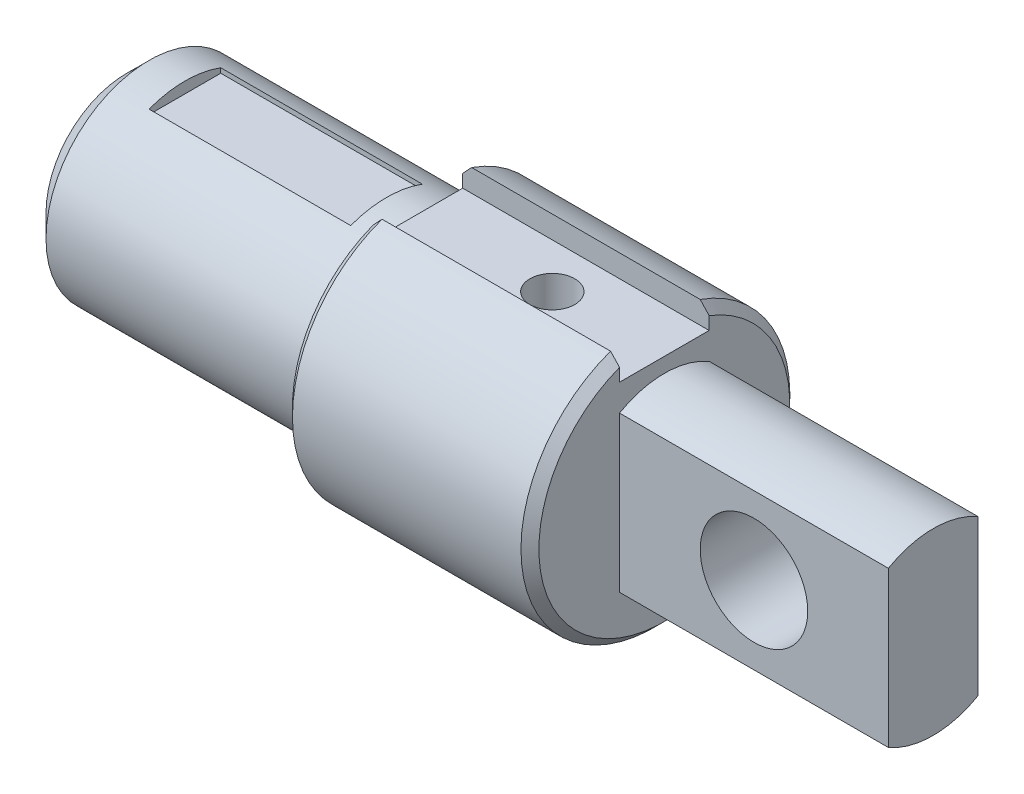
SolidWorks part; units mm, degrees
ref_plane "Спереди" through (0, 0, 0) normal (0, 0, 1) x (1, 0, 0)
ref_plane "Сверху" through (0, 0, 0) normal (0, 1, 0) x (1, 0, 0)
ref_plane "Справа" through (0, 0, 0) normal (1, 0, 0) x (0, 0, -1)
sketch "Эскиз1" plane through (0, 0, 0) normal (0, 0, 1) x (1, 0, 0)
  line L0 (0, 0) -> (-96.5352, 0) construction
  line L1 (0, 0) -> (0, 23)
  line L2 (0, 23) -> (65, 23)
  line L3 (65, 23) -> (65, 30)
  line L4 (65, 30) -> (120, 30)
  line L5 (120, 30) -> (120, 20)
  line L6 (120, 20) -> (180, 20)
  line L7 (180, 20) -> (180, 0)
  line L8 (180, 0) -> (0, 0)
  dimension "D1" = 46
  dimension "D2" = 60
  dimension "D3" = 40
  dimension "D4" = 65
  dimension "D5" = 60
  dimension "D6" = 180
revolve "Повернуть1" add sketch "Эскиз1" angle 360 about L0
sketch "Эскиз2" plane through (0, 0, 0) normal (0, 0, 1) x (1, 0, 0)
  line L0 (65, 23) -> (0, 23) construction
  line L1 (13, 23) -> (58, 23)
  line L2 (13, 23) -> (13, 20.5)
  line L3 (13, 20.5) -> (58, 20.5)
  line L4 (58, 23) -> (58, 20.5)
  line L5 (65, 30) -> (65, -30) construction
  dimension "D1" = 2.5
  dimension "D2" = 45
  dimension "D3" = 7
extrude "Вырез-Вытянуть1" cut sketch "Эскиз2" against normal mid plane 16
sketch "Эскиз4" plane through (65, 0, 0) normal (-1, 0, 0) x (0, 0, 1)
  line L0 (0, 30) -> (0, 0) construction
  line L2 (-10, 23.2843) -> (10, 23.2843)
  line L3 (-10, 23.2843) -> (-10, 30)
  line L4 (-10, 30) -> (10, 30)
  line L5 (10, 23.2843) -> (10, 30)
  line L6 (-10, 23.2843) -> (10, 30) construction
  line L7 (-10, 30) -> (10, 23.2843) construction
  circle A0 centre (0, 0) radius 30 construction
  point P5 (0, 26.6421)
  point P10 (10, 28.2843)
  dimension "D1" = 20
  dimension "D2" = 5
extrude "Вырез-Вытянуть2" cut sketch "Эскиз4" against normal through all
hole_wizard "Диаметр отверстия Ø10.0 (10)1" positions "Эскиз5" profile "Эскиз6" hole size "Ø10.0" standard "ISO"
sketch "Эскиз5" plane through (0, 23.2843, 0) normal (0, 1, 0) x (1, 0, 0)
  line L0 (65, 10) -> (65, -10) construction
  line L1 (65, 0) -> (120, 0) construction
  line L2 (65, 23) -> (65, -23) construction
  line L3 (120, -10) -> (120, 10) construction
  point P0 (95, 0)
  dimension "D1" = 30
sketch "Эскиз6" plane through (95, 23.2843, 0) normal (1, 0, 0) x (0, 0, 1)
  line L0 (0, 0) -> (0, 38.0043)
  line L1 (0, 38.0043) -> (5, 35)
  line L2 (5, 35) -> (5, 0)
  line L5 (5, 0) -> (0, 0)
  line L10 (0, 38.0043) -> (-5, 35) construction
  line L11 (0, -6.35) -> (0, 107.95) construction
  dimension "Диаметр отверстия" = 10
  dimension "Глубина отверстия" = 35
  dimension "Угол заточки сверла" = 118
sketch "Эскиз7" plane through (180, 0, 0) normal (1, 0, 0) x (0, 0, -1)
  line L0 (-10, 17.3205) -> (-10, -17.3205)
  line L1 (-10, 28.2843) -> (-10, 23.2843) construction
  circle A0 centre (0, 0) radius 20 construction
extrude "Вырез-Вытянуть3" cut sketch "Эскиз7" along direction (1, 0, 0) on the side against the normal blind 60 and the other way through all flip side to cut
mirror "Зеркальное отражение1" about plane through (0, 0, 0) normal (0, 0, 1) of "Вырез-Вытянуть3"
hole_wizard "Диаметр отверстия Ø24.0 (24)1" positions "Эскиз8" profile "Эскиз9" hole size "Ø24.0" standard "ISO" end condition through all
sketch "Эскиз8" plane through (0, 0, 10) normal (0, 0, 1) x (1, 0, 0)
  line L0 (120, 0) -> (180, 0) construction
  line L1 (120, 17.3205) -> (120, -17.3205) construction
  line L2 (180, 17.3205) -> (180, -17.3205) construction
  point P0 (150, 0)
  dimension "D1" = 30
sketch "Эскиз9" plane through (150, 0, 10) normal (1, 0, 0) x (0, -1, 0)
  line L0 (0, 0) -> (0, 40)
  line L1 (0, 40) -> (12, 40)
  line L2 (12, 40) -> (12, 0)
  line L5 (12, 0) -> (0, 0)
  line L11 (0, -6.35) -> (0, 107.95) construction
  dimension "Диаметр сквозного отверстия" = 24
  dimension "Глубина сквозного отверстия" = 40
chamfer "Фаска1" distance 5 angle 45 1 edges at (0, 0, -23)
chamfer "Фаска2" distance 2 angle 45 2 edges at (120, -30, 0) (65, -30, 0)
